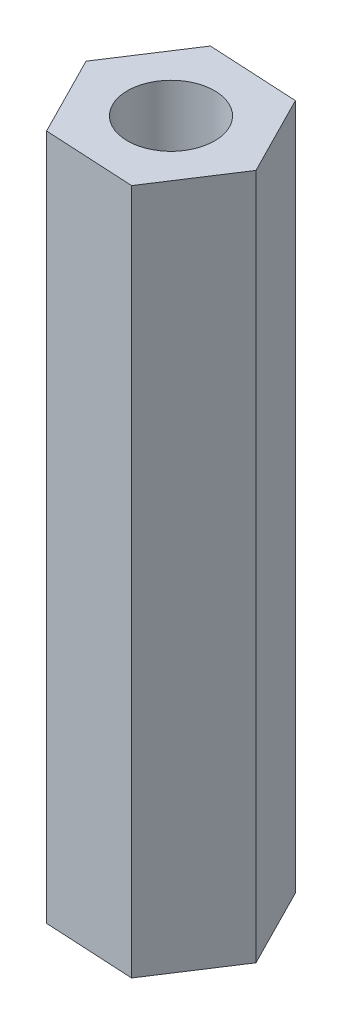
SolidWorks part; units mm, degrees
ref_plane "前视基准面" through (0, 0, 0) normal (0, 0, 1) x (1, 0, 0)
ref_plane "上视基准面" through (0, 0, 0) normal (0, 1, 0) x (1, 0, 0)
ref_plane "右视基准面" through (0, 0, 0) normal (1, 0, 0) x (0, 0, -1)
other "Configuration Table"
sketch "草图1" plane through (0, 0, 0) normal (0, 1, 0) x (1, 0, 0)
  line L1 (3.4015, -0.1819) -> (1.8583, 2.8548)
  line L2 (1.8583, 2.8548) -> (-1.5432, 3.0368)
  line L3 (-1.5432, 3.0368) -> (-3.4015, 0.1819)
  line L4 (-3.4015, 0.1819) -> (-1.8583, -2.8548)
  line L5 (-1.8583, -2.8548) -> (1.5432, -3.0368)
  line L6 (1.5432, -3.0368) -> (3.4015, -0.1819)
  circle A0 centre (0, 0) radius 2.95 construction
  dimension "D1" = 5.9
extrude "凸台-拉伸1" add sketch "草图1" along normal blind 26
hole_wizard "M4 螺纹孔1" positions "草图2" profile "草图3" tap size "M4" standard "GB" end condition through all
sketch "草图2" plane through (0, 26, 0) normal (0, 1, 0) x (1, 0, 0)
  point P0 (0, 0)
sketch "草图3" plane through (0, 26, 0) normal (1, 0, 0) x (0, 0, 1)
  line L0 (0, 0) -> (0, 26)
  line L1 (0, 26) -> (1.65, 26)
  line L2 (1.65, 26) -> (1.65, 0)
  line L5 (1.65, 0) -> (0, 0)
  line L11 (0, -6.35) -> (0, 107.95) construction
  dimension "通孔螺纹孔钻头直径" = 3.3
  dimension "通孔螺纹孔钻头深度" = 26
cosmetic thread "孔螺纹线1" parameters "D2"=4
